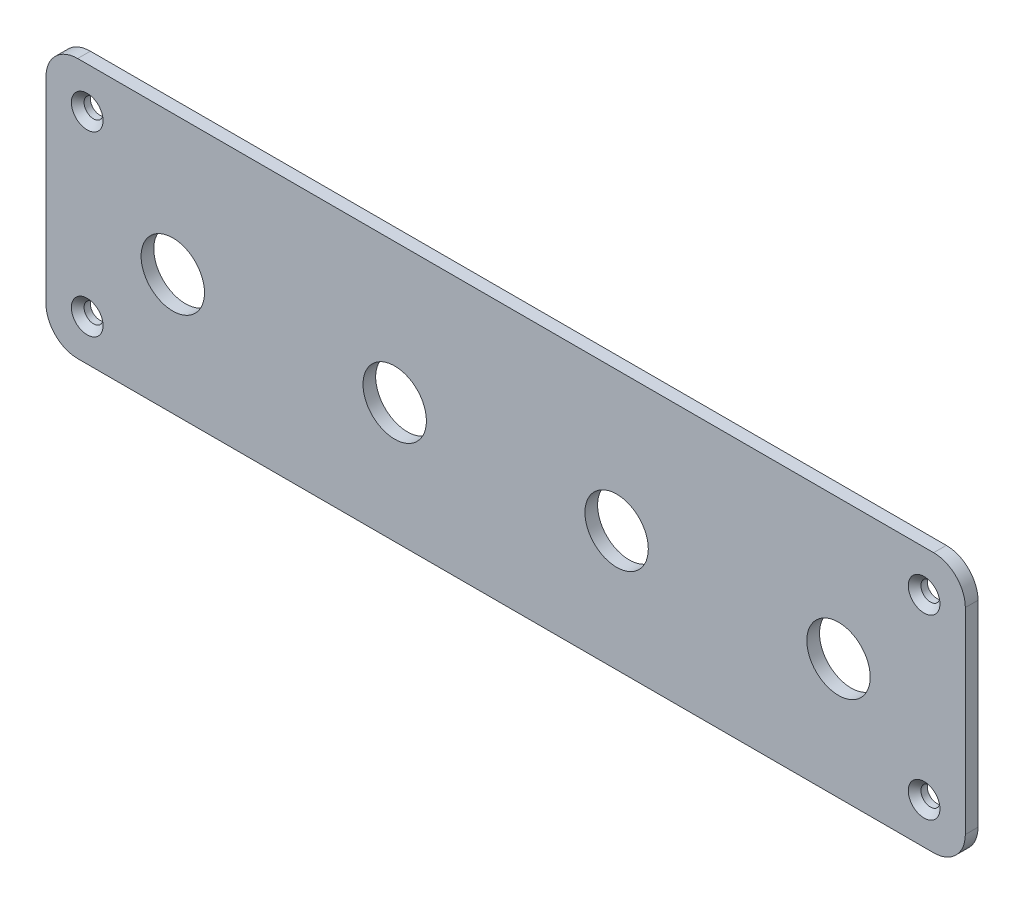
SolidWorks part; units mm, degrees
ref_plane "Alzado" through (0, 0, 0) normal (0, 0, 1) x (1, 0, 0)
ref_plane "Planta" through (0, 0, 0) normal (0, 1, 0) x (1, 0, 0)
ref_plane "Vista lateral" through (0, 0, 0) normal (1, 0, 0) x (0, 0, -1)
sketch "Croquis1" plane through (0, 0, 0) normal (0, 0, 1) x (1, 0, 0)
  line L1 (-67.5, -20.5) -> (67.5, -20.5)
  line L2 (-72.5, -15.5) -> (-72.5, 15.5)
  line L3 (-67.5, 20.5) -> (67.5, 20.5)
  line L4 (72.5, -15.5) -> (72.5, 15.5)
  line L5 (-72.5, -20.5) -> (72.5, 20.5) construction
  line L6 (-72.5, 20.5) -> (72.5, -20.5) construction
  line L7 (-70, -18) -> (70, -18) construction
  line L8 (-70, -18) -> (-70, 18) construction
  line L9 (-70, 18) -> (70, 18) construction
  line L10 (70, -18) -> (70, 18) construction
  line L11 (-70, -18) -> (70, 18) construction
  line L12 (-70, 18) -> (70, -18) construction
  arc A0 (67.5, 20.5) -> (72.5, 15.5) centre (67.5, 15.5) cw
  arc A1 (72.5, -15.5) -> (67.5, -20.5) centre (67.5, -15.5) cw
  arc A2 (-67.5, -20.5) -> (-72.5, -15.5) centre (-67.5, -15.5) cw
  arc A3 (-72.5, 15.5) -> (-67.5, 20.5) centre (-67.5, 15.5) cw
  circle A4 centre (-52.5, -1.5) radius 5
  circle A5 centre (-17.5, -1.5) radius 5
  circle A6 centre (17.5, -1.5) radius 5
  circle A7 centre (52.5, -1.5) radius 5
  circle A9 centre (-66, 14) radius 1.5
  circle A10 centre (-66, -14) radius 1.5
  circle A11 centre (66, -14) radius 1.5
  circle A12 centre (66, 14) radius 1.5
  point P0 (0, 0)
  point P31 (0, 0)
  point P41 (0, 0)
  point P42 (0, 0)
  point P43 (0, 0)
  point P44 (0, 0)
  dimension "D3" = 5
  dimension "D5" = 36
  dimension "D6" = 10
  dimension "D8" = 35
  dimension "D9" = 35
  dimension "D14" = 3
  dimension "D15" = 4
  dimension "D16" = 4
  dimension "D17" = 4
  dimension "D18" = 4
  dimension "D1" = 145
  dimension "D2" = 41
  dimension "D4" = 140
  dimension "D7" = 35
  dimension "D10" = 16.5
  dimension "D11" = 17.5
extrude "Saliente-Extruir1" add sketch "Croquis1" against normal blind 2
chamfer "Chaflán1" distance 1 angle 45 4 edges at (67.5, -14, 0) (67.5, 14, 0) (-64.5, -14, 0) (-64.5, 14, 0)
